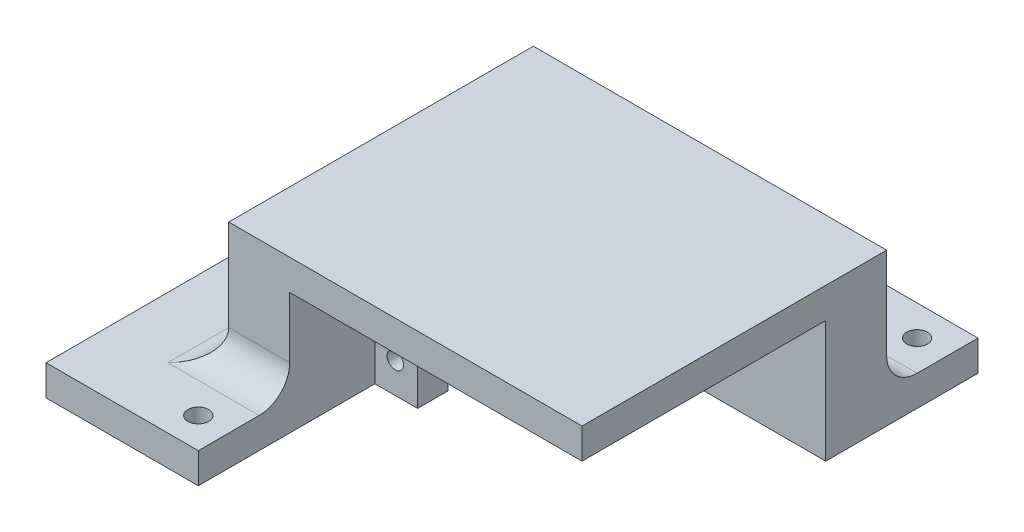
SolidWorks part; units mm, degrees
ref_plane "前视基准面" through (0, 0, 0) normal (0, 0, 1) x (1, 0, 0)
ref_plane "上视基准面" through (0, 0, 0) normal (0, 1, 0) x (1, 0, 0)
ref_plane "右视基准面" through (0, 0, 0) normal (1, 0, 0) x (0, 0, -1)
sketch "草图1" plane through (0, 0, 0) normal (0, 1, 0) x (1, 0, 0)
  line L1 (-24, -27.5) -> (24, -27.5)
  line L2 (-24, -27.5) -> (-24, 27.5)
  line L3 (-24, 27.5) -> (24, 27.5)
  line L4 (24, -27.5) -> (24, 27.5)
  line L5 (-24, -27.5) -> (24, 27.5) construction
  line L6 (-24, 27.5) -> (24, -27.5) construction
  line L7 (24, 27.5) -> (-49, 27.5)
  line L8 (24, 27.5) -> (24, 52.5)
  line L9 (24, 52.5) -> (-49, 52.5)
  line L10 (-49, 27.5) -> (-49, 52.5)
  line L11 (-49, 52.5) -> (-24, 52.5)
  line L12 (-49, 52.5) -> (-49, -27.5)
  line L13 (-49, -27.5) -> (-24, -27.5)
  line L14 (-24, 52.5) -> (-24, -27.5)
  circle A0 centre (19, 47.5) radius 1.7
  circle A1 centre (-29, -22.5) radius 1.7
  circle A2 centre (-44, 47.5) radius 1.7
  point P0 (0, 0)
  dimension "D5" = 3.4
  dimension "D6" = 3.4
  dimension "D7" = 3.4
  dimension "D1" = 48
  dimension "D2" = 55
  dimension "D3" = 25
  dimension "D4" = 25
  dimension "D8" = 5
  dimension "D9" = 5
  dimension "D10" = 5
  dimension "D11" = 5
  dimension "D12" = 5
  dimension "D13" = 5
extrude "凸台-拉伸1" add sketch "草图1" along normal blind 5 contours L9 L14 L3 L8 | L14 L9 L10 L7 | L12 L13 L2 L7
sketch "草图2" plane through (0, 5, 0) normal (0, 1, 0) x (1, 0, 0)
  line L0 (-24, -27.5) -> (-24, 27.5) construction
  line L1 (-24, -12.5) -> (-34, -12.5)
  line L2 (-24, -12.5) -> (-24, 37.5)
  line L3 (-24, 37.5) -> (-34, 37.5)
  line L4 (-34, -12.5) -> (-34, 37.5)
  line L5 (24, 27.5) -> (-34, 27.5)
  line L6 (24, 27.5) -> (24, 37.5)
  line L7 (24, 37.5) -> (-34, 37.5)
  line L8 (-34, 27.5) -> (-34, 37.5)
  line M12 (-24, -27.5) -> (-24, 27.5)
  line M13 (-24, 27.5) -> (24, 27.5)
  line M14 (24, 27.5) -> (24, 52.5)
  dimension "D1" = 10
  dimension "D2" = 10
  dimension "D3" = 50
extrude "凸台-拉伸2" add sketch "草图2" along normal blind 15 contours L7 L2 M14 M13 | L5 L2 L3 L4 | L5 L4 L1 M12
sketch "草图3" plane through (0, 20, 0) normal (0, 1, 0) x (1, 0, 0)
  line L0 (-24, -12.5) -> (-34, -12.5) construction
  line L1 (-34, 37.5) -> (24, 37.5)
  line L2 (-34, 37.5) -> (-34, -12.5)
  line L3 (-34, -12.5) -> (24, -12.5)
  line L4 (24, 37.5) -> (24, -12.5)
  line L5 (-24, -12.5) -> (-34, -12.5) construction
extrude "凸台-拉伸3" add sketch "草图3" along normal blind 5
sketch "草图4" plane through (-24, 0, 0) normal (1, 0, 0) x (0, 0, -1)
  line L0 (-12.5, 20) -> (27.5, 20) construction
  line L1 (1.5, 20) -> (6.5, 20)
  line L2 (1.5, 20) -> (1.5, 0)
  line L3 (1.5, 0) -> (6.5, 0)
  line L4 (6.5, 20) -> (6.5, 0)
  line L5 (-27.5, 0) -> (27.5, 0) construction
  line L6 (27.5, 20) -> (27.5, 0) construction
  dimension "D1" = 26
  dimension "D2" = 5
extrude "凸台-拉伸4" add sketch "草图4" along normal blind 7
sketch "草图5" plane through (0, 0, -1.5) normal (0, 0, 1) x (1, 0, 0)
  line L0 (-17, 20) -> (-24, 20) construction
  line L1 (-24, 20) -> (-24, 0) construction
  circle A0 centre (-20.65, 5) radius 1.35
  circle A1 centre (-20.65, 15) radius 1.35
  dimension "D5" = 2.7
  dimension "D6" = 2.7
  dimension "D1" = 5
  dimension "D2" = 10
  dimension "D3" = 3.35
  dimension "D4" = 3.35
extrude "切除-拉伸1" cut sketch "草图5" against normal blind 7
fillet "圆角1" radius 5 3 edges at (-5, 5, -37.5) (-29, 5, 12.5) (-34, 5, -12.5)
